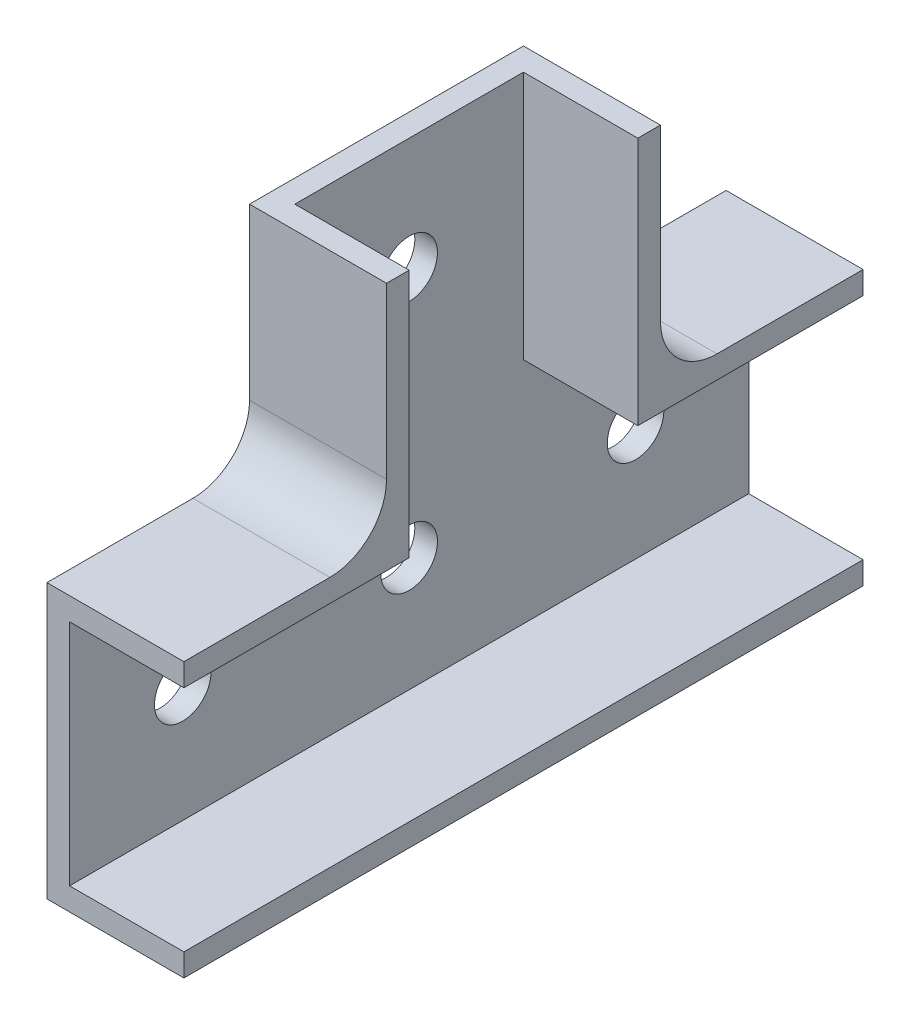
SolidWorks part; units mm, degrees
ref_plane "前视基准面" through (0, 0, 0) normal (0, 0, 1) x (1, 0, 0)
ref_plane "上视基准面" through (0, 0, 0) normal (0, 1, 0) x (1, 0, 0)
ref_plane "右视基准面" through (0, 0, 0) normal (1, 0, 0) x (0, 0, -1)
other "Configuration Table"
sketch "草图2" plane through (0, 0, 0) normal (0, 0, 1) x (1, 0, 0)
  line L0 (-12.1, 12.1) -> (12.1, 12.1)
  line L1 (-10.1, -10.1) -> (10.1, -10.1)
  line L2 (-10.1, -10.1) -> (-10.1, 10.1)
  line L3 (-10.1, 10.1) -> (10.1, 10.1)
  line L4 (10.1, -10.1) -> (10.1, 10.1)
  line L5 (-10.1, -10.1) -> (10.1, 10.1) construction
  line L6 (-10.1, 10.1) -> (10.1, -10.1) construction
  line L7 (12.1, -12.1) -> (12.1, 12.1)
  line L8 (-12.1, -12.1) -> (12.1, -12.1)
  line L9 (-12.1, -12.1) -> (-12.1, 12.1)
  point P0 (0, 0)
  dimension "D1" = 20.2
  dimension "D2" = 20.2
  dimension "D3" = 2
extrude "凸台-拉伸4" add sketch "草图2" along normal blind 100
sketch "草图6" plane through (0, 12.1, 0) normal (0, 1, 0) x (1, 0, 0)
  line L0 (-1012.1, -50) -> (48987.9, -50) construction
  line L1 (-12.1, -100) -> (-12.1, 0) construction
  line L2 (0, -1000) -> (0, 49000) construction
  line L3 (-12.1, -37.9) -> (12.1, -37.9)
  line L4 (-10.1, -60.1) -> (10.1, -60.1)
  line L5 (-10.1, -60.1) -> (-10.1, -39.9)
  line L6 (-10.1, -39.9) -> (10.1, -39.9)
  line L7 (10.1, -60.1) -> (10.1, -39.9)
  line L8 (-10.1, -60.1) -> (10.1, -39.9) construction
  line L9 (-10.1, -39.9) -> (10.1, -60.1) construction
  line L10 (12.1, -62.1) -> (12.1, -37.9)
  line L11 (-12.1, -62.1) -> (12.1, -62.1)
  line L12 (-12.1, -62.1) -> (-12.1, -37.9)
  point P5 (-12.1, -50)
  point P6 (0, -50)
  dimension "D1" = 20.2
  dimension "D2" = 20.2
  dimension "D3" = 2
extrude "凸台-拉伸5" add sketch "草图6" along normal blind 40
sketch "草图7" plane through (-12.1, 0, 0) normal (-1, 0, 0) x (0, 0, 1)
  line L0 (-1000, 0) -> (49000, 0) construction
  line L1 (50, -947.9) -> (50, 49052.1) construction
  line L2 (37.9, 52.1) -> (62.1, 52.1) construction
  circle A0 centre (10, 0) radius 2.5
  circle A1 centre (30, 0) radius 2.5
  circle A2 centre (90, 0) radius 2.5
  circle A3 centre (70, 0) radius 2.5
  circle A4 centre (50, 42.1) radius 2.5
  circle A5 centre (50, 22.1) radius 2.5
  point P8 (50, 52.1)
  dimension "D1" = 5
  dimension "D2" = 5
  dimension "D5" = 5
  dimension "D6" = 5
  dimension "D3" = 10
  dimension "D4" = 20
  dimension "D7" = 10
  dimension "D8" = 20
extrude "切除-拉伸1" cut sketch "草图7" against normal blind 40
sketch "草图8" plane through (12.1, 0, 0) normal (1, 0, 0) x (0, 0, -1)
  line L0 (-1100, 0) -> (48900, 0) construction
  line L1 (-100, -12.1) -> (-100, 12.1) construction
  line L2 (-50, -947.9) -> (-50, 49052.1) construction
  line L3 (-62.1, 52.1) -> (-37.9, 52.1) construction
  circle A0 centre (-50, 0) radius 2.5
  point P5 (-100, 0)
  point P10 (-50, 52.1)
  dimension "D1" = 5
extrude "切除-拉伸2" cut sketch "草图8" against normal blind 40
sketch "草图9" plane through (12.1, 0, 0) normal (1, 0, 0) x (0, 0, -1)
  line L0 (-100, 12.1) -> (-80, 12.1)
  line L1 (-100, 12.1) -> (-62.1, 12.1) construction
  line L2 (-100, -12.1) -> (0, -12.1) construction
  line L3 (-80, 12.1) -> (-100, 12.1)
  line L4 (-80, 12.1) -> (-80, -12.1)
  line L5 (-80, -12.1) -> (-100, -12.1)
  line L6 (-100, 12.1) -> (-100, -12.1)
  line L7 (-50, -947.9) -> (-50, 49052.1) construction
  line L8 (-62.1, 52.1) -> (-37.9, 52.1) construction
  line L9 (0, 12.1) -> (0, -12.1)
  line L10 (-20, -12.1) -> (0, -12.1)
  line L11 (0, 12.1) -> (-20, 12.1)
  line L12 (-20, 12.1) -> (-20, -12.1)
  point P14 (-50, 52.1)
  circle M6 centre (-10, 0) radius 2.5
  circle M9 centre (-90, 0) radius 2.5
  line M12 (0, -12.1) -> (0, 12.1)
  line M13 (0, 12.1) -> (-37.9, 12.1)
  line M17 (-62.1, 12.1) -> (-100, 12.1)
  line M18 (-100, 12.1) -> (-100, -12.1)
  line M19 (-100, -12.1) -> (0, -12.1)
  dimension "D1" = 20
extrude "切除-拉伸3" cut sketch "草图9" against normal blind 40 contours L12 M13 M19 M12 M6 | L4 M17 M18 M19 M9
sketch "草图10" plane through (12.1, 0, 0) normal (1, 0, 0) x (0, 0, -1)
  line L0 (-62.1, 52.1) -> (-62.1, 32.1)
  line L1 (-62.1, 52.1) -> (-62.1, 12.1) construction
  line L3 (-62.1, 32.1) -> (-37.9, 32.1)
  line L4 (-62.1, 32.1) -> (-62.1, 52.1)
  line L5 (-62.1, 52.1) -> (-37.9, 52.1)
  line L6 (-37.9, 32.1) -> (-37.9, 52.1)
  circle M2 centre (-50, 42.1) radius 2.5
  line M10 (-37.9, 12.1) -> (-37.9, 52.1)
  line M11 (-37.9, 52.1) -> (-62.1, 52.1)
  line M12 (-62.1, 52.1) -> (-62.1, 12.1)
  dimension "D1" = 20
extrude "切除-拉伸4" cut sketch "草图10" against normal blind 40 contours L3 M12 M10 M11 M2
sketch "草图11" plane through (12.1, 0, 0) normal (1, 0, 0) x (0, 0, -1)
  line L1 (-85.9106, 32.933) -> (-16.0894, 32.933)
  line L2 (-85.9106, 32.933) -> (-85.9106, -15.733)
  line L3 (-85.9106, -15.733) -> (-16.0894, -15.733)
  line L4 (-16.0894, 32.933) -> (-16.0894, -15.733)
extrude "切除-拉伸5" cut sketch "草图11" against normal blind 12.1
sketch "草图12" plane through (0, 0, 0) normal (1, 0, 0) x (0, 0, -1)
  line L0 (-60.1, 12.1) -> (-39.9, 12.1)
  line L1 (-39.9, 12.1) -> (-39.9, 10.1)
  line L2 (-20, 10.1) -> (-80, 10.1) construction
  line L3 (-39.9, 10.1) -> (-60.1, 10.1)
  line L4 (-80, 10.1) -> (-20, 10.1) construction
  line L5 (-60.1, 10.1) -> (-60.1, 12.1)
extrude "切除-拉伸6" cut sketch "草图12" against normal blind 10
sketch "草图13" plane through (-10, 0, 0) normal (1, 0, 0) x (0, 0, -1)
  line L1 (-60.1, 12.1) -> (-39.9, 12.1)
  line L2 (-60.1, 12.1) -> (-60.1, 10.1)
  line L3 (-60.1, 10.1) -> (-39.9, 10.1)
  line L4 (-39.9, 12.1) -> (-39.9, 10.1)
extrude "切除-拉伸7" cut sketch "草图13" against normal blind 0.1
fillet "圆角1" radius 5 1 edges at (-6.05, 12.1, 37.9)
fillet "圆角2" radius 5 1 edges at (-6.05, 12.1, 62.1)
